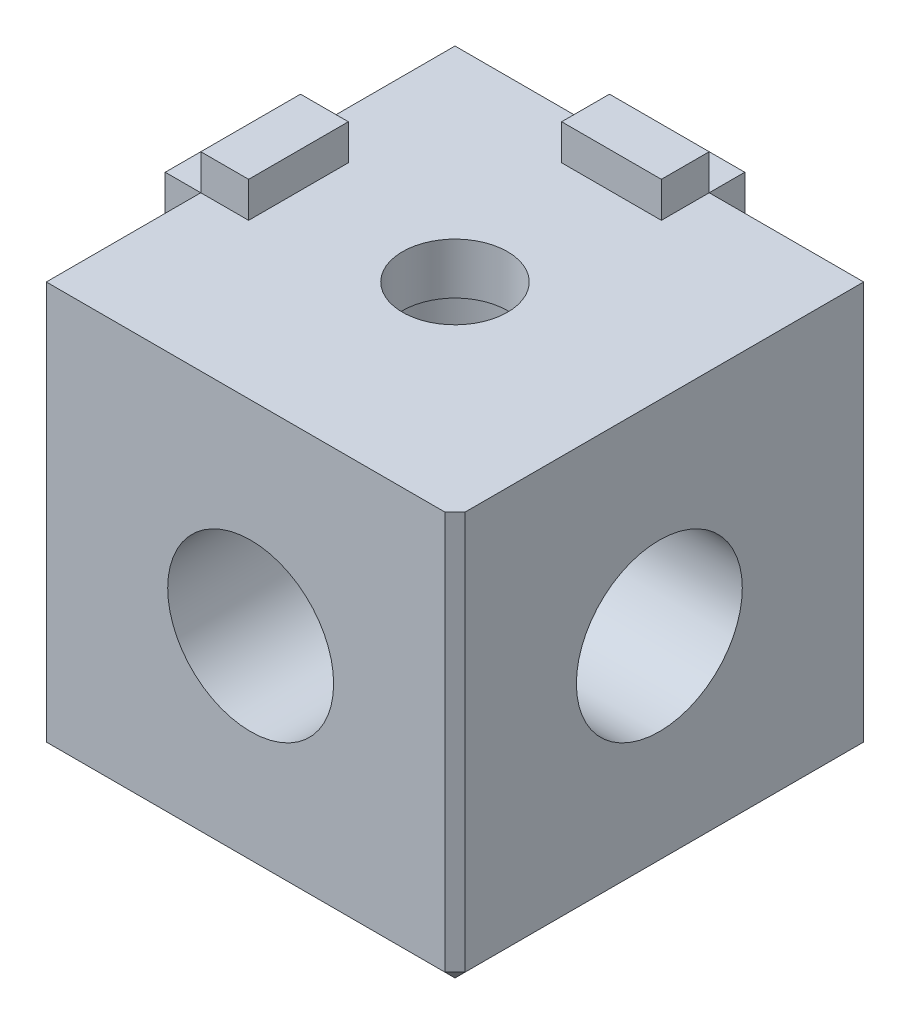
SolidWorks part; units mm, degrees
material "6105-T5"
ref_plane "Front Plane" through (0, 0, 0) normal (0, 0, 1) x (1, 0, 0)
ref_plane "Top Plane" through (0, 0, 0) normal (0, 1, 0) x (1, 0, 0)
ref_plane "Right Plane" through (0, 0, 0) normal (1, 0, 0) x (0, 0, -1)
sketch "Sketch1" plane through (0, 0, 0) normal (0, 0, 1) x (1, 0, 0)
  line L1 (-12.7, -12.7) -> (12.7, -12.7)
  line L2 (-12.7, -12.7) -> (-12.7, 12.7)
  line L3 (-12.7, 12.7) -> (12.7, 12.7)
  line L4 (12.7, -12.7) -> (12.7, 12.7)
  line L5 (-12.7, -12.7) -> (12.7, 12.7) construction
  line L6 (-12.7, 12.7) -> (12.7, -12.7) construction
  point P0 (0, 0)
  dimension "D1" = 25.4
  dimension "D2" = 25.4
extrude "Boss-Extrude1" add sketch "Sketch1" along normal mid plane 25.4
hole_wizard "Hole1" positions "Sketch3" profile "Sketch2" legacy
sketch "Sketch3" plane through (0, 0, 12.7) normal (0, 0, 1) x (1, 0, 0)
  point P0 (0, 0)
sketch "Sketch2" plane through (0, 0, 12.7) normal (1, 0, 0) x (0, -1, 0)
  line L0 (0, 0) -> (0, 100)
  line L1 (0, 100) -> (3.2639, 100)
  line L2 (3.2639, 100) -> (3.2639, 22.225)
  line L3 (3.2639, 22.225) -> (5.1562, 22.225)
  line L4 (5.1562, 22.225) -> (5.1562, 0)
  line L5 (5.1562, 0) -> (0, 0)
  line L6 (0, 110) -> (0, -10) construction
  dimension "Diameter" = 6.5278
  dimension "Depth" = 100
  dimension "C-Bore Diameter" = 10.3124
  dimension "C-Bore Depth" = 22.225
hole_wizard "Hole2" positions "Sketch5" profile "Sketch4" legacy
sketch "Sketch5" plane through (12.7, 0, 0) normal (1, 0, 0) x (0, 0, -1)
  point P0 (0, 0)
sketch "Sketch4" plane through (12.7, 0, 0) normal (0, 1, 0) x (0, 0, -1)
  line L0 (0, 0) -> (0, 100)
  line L1 (0, 100) -> (3.2639, 100)
  line L2 (3.2639, 100) -> (3.2639, 22.225)
  line L3 (3.2639, 22.225) -> (5.1562, 22.225)
  line L4 (5.1562, 22.225) -> (5.1562, 0)
  line L5 (5.1562, 0) -> (0, 0)
  line L6 (0, 110) -> (0, -10) construction
  dimension "Diameter" = 6.5278
  dimension "Depth" = 100
  dimension "C-Bore Diameter" = 10.3124
  dimension "C-Bore Depth" = 22.225
hole_wizard "Hole3" positions "Sketch7" profile "Sketch6" legacy
sketch "Sketch7" plane through (0, -12.7, 0) normal (0, -1, 0) x (1, 0, 0)
  point P0 (0, 0)
sketch "Sketch6" plane through (0, -12.7, 0) normal (1, 0, 0) x (0, 0, -1)
  line L0 (0, 0) -> (0, 100)
  line L1 (0, 100) -> (3.2639, 100)
  line L2 (3.2639, 100) -> (3.2639, 22.225)
  line L3 (3.2639, 22.225) -> (5.1562, 22.225)
  line L4 (5.1562, 22.225) -> (5.1562, 0)
  line L5 (5.1562, 0) -> (0, 0)
  line L6 (0, 110) -> (0, -10) construction
  dimension "Diameter" = 6.5278
  dimension "Depth" = 100
  dimension "C-Bore Diameter" = 10.3124
  dimension "C-Bore Depth" = 22.225
sketch "Sketch8" plane through (0, 12.7, 0) normal (0, 1, 0) x (1, 0, 0)
  line L0 (12.7, 12.7) -> (-12.7, 12.7) construction
  line L1 (-3.0988, 9.7282) -> (3.0988, 9.7282)
  line L2 (-3.0988, 9.7282) -> (-3.0988, 12.7)
  line L4 (3.0988, 9.7282) -> (3.0988, 12.7)
  line L5 (-3.0988, 9.7282) -> (0, 12.7) construction
  line L6 (0, 12.7) -> (3.0988, 9.7282) construction
  line L7 (3.0988, 12.7) -> (-3.0988, 12.7)
  point P0 (0, 12.7)
  dimension "D1" = 6.1976
  dimension "D2" = 2.9718
extrude "Boss-Extrude2" add sketch "Sketch8" along normal blind 2.2098
pattern_circular "CirPattern1" count 2 over 270 about axis through (0, 0, 0) along (0, 1, 0) of "Boss-Extrude2"
sketch "Sketch9" plane through (-12.7, 0, 0) normal (-1, 0, 0) x (0, 0, 1)
  line L0 (-3.0988, 12.7) -> (3.0988, 12.7)
  line L1 (3.0988, 12.7) -> (3.0988, 9.7282)
  line L2 (3.0988, 9.7282) -> (-3.0988, 9.7282)
  line L3 (-3.0988, 9.7282) -> (-3.0988, 12.7)
  dimension "D1" = 2.9718
extrude "Boss-Extrude3" add sketch "Sketch9" along normal blind 2.2098
pattern_circular "CirPattern2" count 2 over 270 about axis through (0, 0, 0) along (1, 0, 0) of "Boss-Extrude3"
sketch "Sketch10" plane through (0, 0, -12.7) normal (0, 0, -1) x (-1, 0, 0)
  line L0 (12.7, 3.0988) -> (12.7, -3.0988)
  line L1 (12.7, -3.0988) -> (9.7282, -3.0988)
  line L2 (9.7282, -3.0988) -> (9.7282, 3.0988)
  line L3 (9.7282, 3.0988) -> (12.7, 3.0988)
  dimension "D1" = 2.9718
extrude "Boss-Extrude4" add sketch "Sketch10" along normal blind 2.2098
pattern_circular "CirPattern3" count 2 over 90 about axis through (0, 0, 0) along (0, 0, 1) of "Boss-Extrude4"
chamfer "Chamfer1" distance 0.635 angle 45 3 edges at (12.7, 0, 12.7) (12.7, -12.7, 0) (0, -12.7, 12.7)
